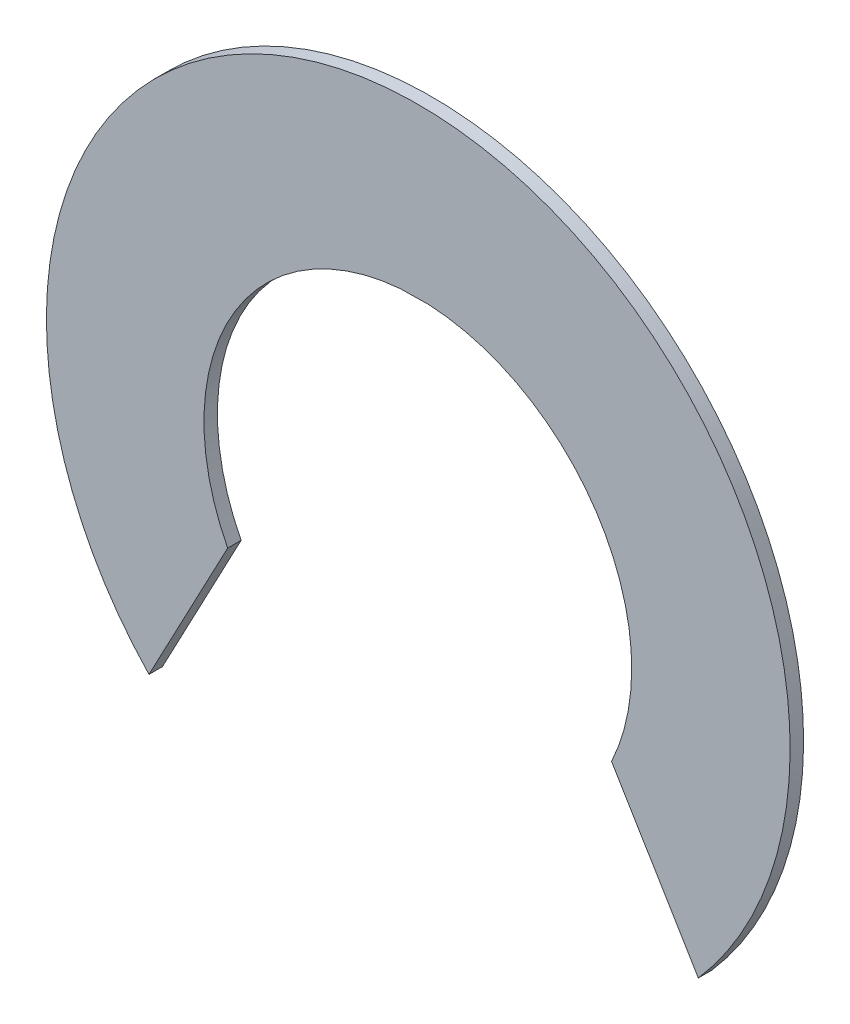
SolidWorks part; units mm, degrees
ref_plane "前视基准面" through (0, 0, 0) normal (0, 0, 1) x (1, 0, 0)
ref_plane "上视基准面" through (0, 0, 0) normal (0, 1, 0) x (1, 0, 0)
ref_plane "右视基准面" through (0, 0, 0) normal (1, 0, 0) x (0, 0, -1)
sketch "草图1" plane through (0, 0, 0) normal (0, 0, 1) x (1, 0, 0)
  line L9 (-5.3977, 62.2272) -> (3.1302, 62.3783)
  line L12 (57.5505, -28.0248) -> (83.3375, -70.8621)
  line L13 (-56.5167, -30.1721) -> (-79.9002, -74.3673)
  arc A1 (-56.5167, -30.1721) -> (-5.3977, 62.2272) centre (-0.0103, -1.0935) cw
  arc A2 (3.1302, 62.3783) -> (57.5505, -28.0248) centre (-0.0103, -1.0935) cw
  arc A4 (-79.9002, -74.3673) -> (83.3375, -70.8621) centre (0.1202, 1.8259) cw
  dimension "D1" = 50
  dimension "D2" = 50
extrude "凸台-拉伸1" add sketch "草图1" along normal blind 4
